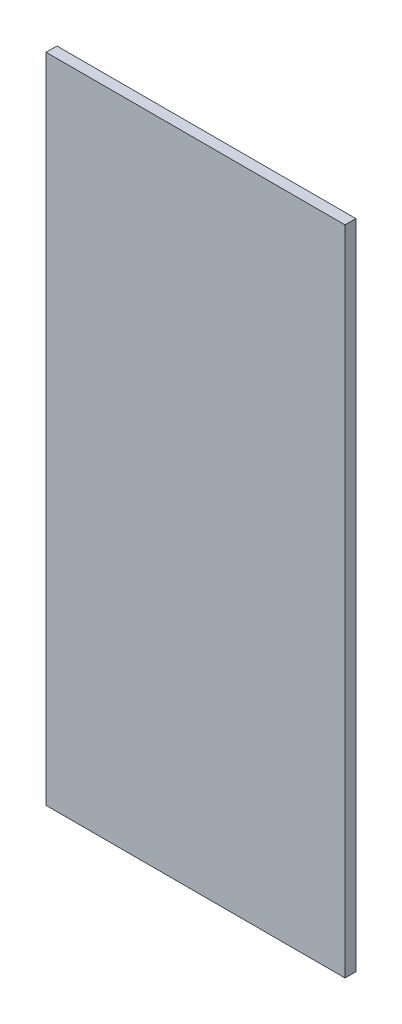
SolidWorks part; units mm, degrees
ref_plane "Płaszczyzna przednia" through (0, 0, 0) normal (0, 0, 1) x (1, 0, 0)
ref_plane "Płaszczyzna górna" through (0, 0, 0) normal (0, 1, 0) x (1, 0, 0)
ref_plane "Płaszczyzna prawa" through (0, 0, 0) normal (1, 0, 0) x (0, 0, -1)
sketch "Szkic1" plane through (0, 0, 0) normal (0, 0, 1) x (1, 0, 0)
  line L0 (-23.4374, -98.1714) -> (31.5626, -98.1714)
  line L1 (31.5626, -98.1714) -> (31.5626, 21.8286)
  line L2 (31.5626, 21.8286) -> (-23.4374, 21.8286)
  line L3 (-23.4374, 21.8286) -> (-23.4374, -98.1714)
  dimension "D1" = 55
  dimension "D2" = 120
  dimension "D3" = 120
  dimension "D4" = 55
extrude "Dodanie-wyciągnięcie1" add sketch "Szkic1" along normal blind 2 contours L3 L0 L1 L2
